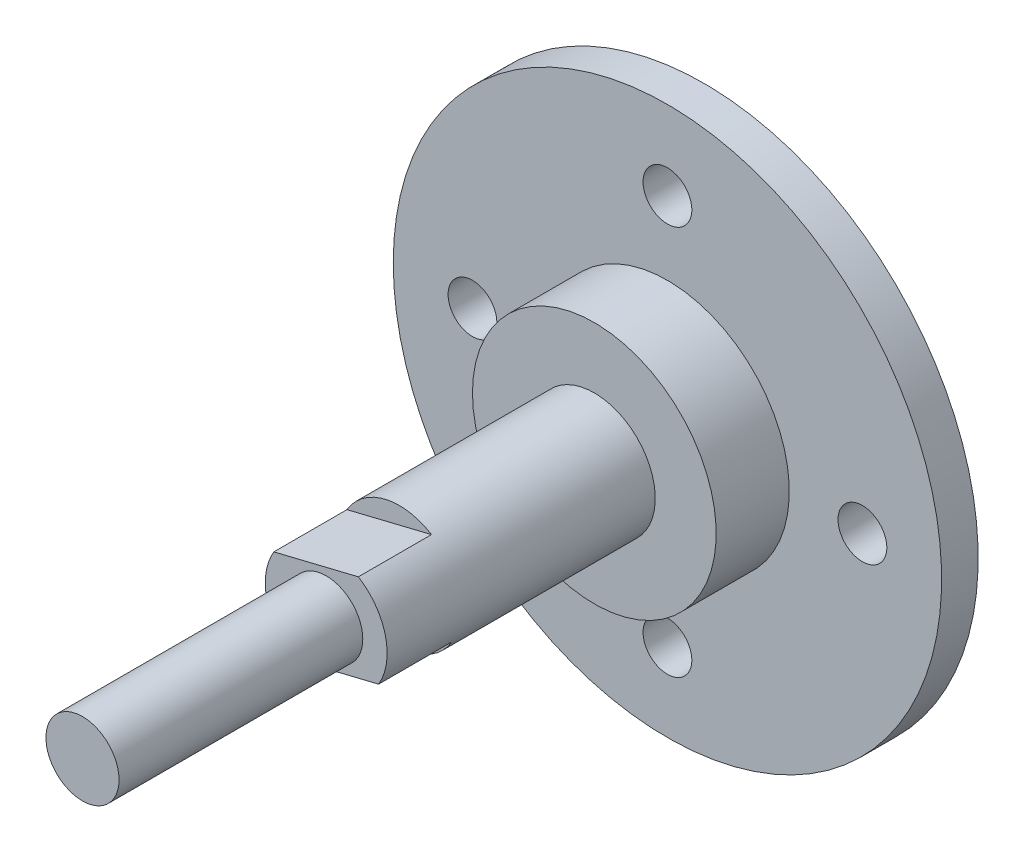
SolidWorks part; units mm, degrees
material "Cast Alloy Steel"
ref_plane "Front Plane" through (0, 0, 0) normal (0, 0, 1) x (1, 0, 0)
ref_plane "Top Plane" through (0, 0, 0) normal (0, 1, 0) x (1, 0, 0)
ref_plane "Right Plane" through (0, 0, 0) normal (1, 0, 0) x (0, 0, -1)
sketch "Sketch1" plane through (0, 0, 0) normal (0, 0, 1) x (1, 0, 0)
  circle A0 centre (0, 0) radius 5
  dimension "D1" = 10
extrude "Boss-Extrude1" add sketch "Sketch1" along normal blind 22
sketch "Sketch2" plane through (0, 0, 22) normal (0, 0, 1) x (1, 0, 0)
  line L0 (2.6383, 4.2473) -> (-4.2992, 2.5528)
  line L1 (-2.6383, -4.2473) -> (4.2992, -2.5528)
  arc A0 (-2.6383, -4.2473) -> (4.2992, -2.5528) centre (0, 0) ccw
  arc A1 (2.6383, 4.2473) -> (-4.2992, 2.5528) centre (0, 0) ccw
  dimension "D2" = 10
  dimension "D3" = 3.5
  dimension "D1" = 3.5
  dimension "D4" = 360
extrude "Cut-Extrude1" cut sketch "Sketch2" against normal blind 6
sketch "Sketch3" plane through (0, 0, 22) normal (0, 0, 1) x (1, 0, 0)
  circle A0 centre (0, 0) radius 3
extrude "Boss-Extrude2" add sketch "Sketch3" along normal blind 20
sketch "Sketch4" plane through (0, 0, 0) normal (0, 0, -1) x (-1, 0, 0)
  circle A0 centre (0, 0) radius 10
  dimension "D1" = 20
extrude "Boss-Extrude3" add sketch "Sketch4" along normal blind 6
sketch "Sketch5" plane through (0, 0, -6) normal (0, 0, -1) x (-1, 0, 0)
  circle A0 centre (0, 0) radius 22.5
  dimension "D1" = 45
extrude "Boss-Extrude4" add sketch "Sketch5" along normal blind 3 contours A0
sketch "Sketch6" plane through (0, 0, -9) normal (0, 0, -1) x (-1, 0, 0)
  circle A0 centre (-16, 0) radius 2
  circle A1 centre (0, 0) radius 22.5 construction
  circle A2 centre (0, 16) radius 2
  circle A3 centre (16, 0) radius 2
  circle A4 centre (0, -16) radius 2
  point P13 (0, 0)
  dimension "D1" = 4
  dimension "D2" = 16
  dimension "D3" = 4
extrude "Cut-Extrude2" cut sketch "Sketch6" against normal blind 3
